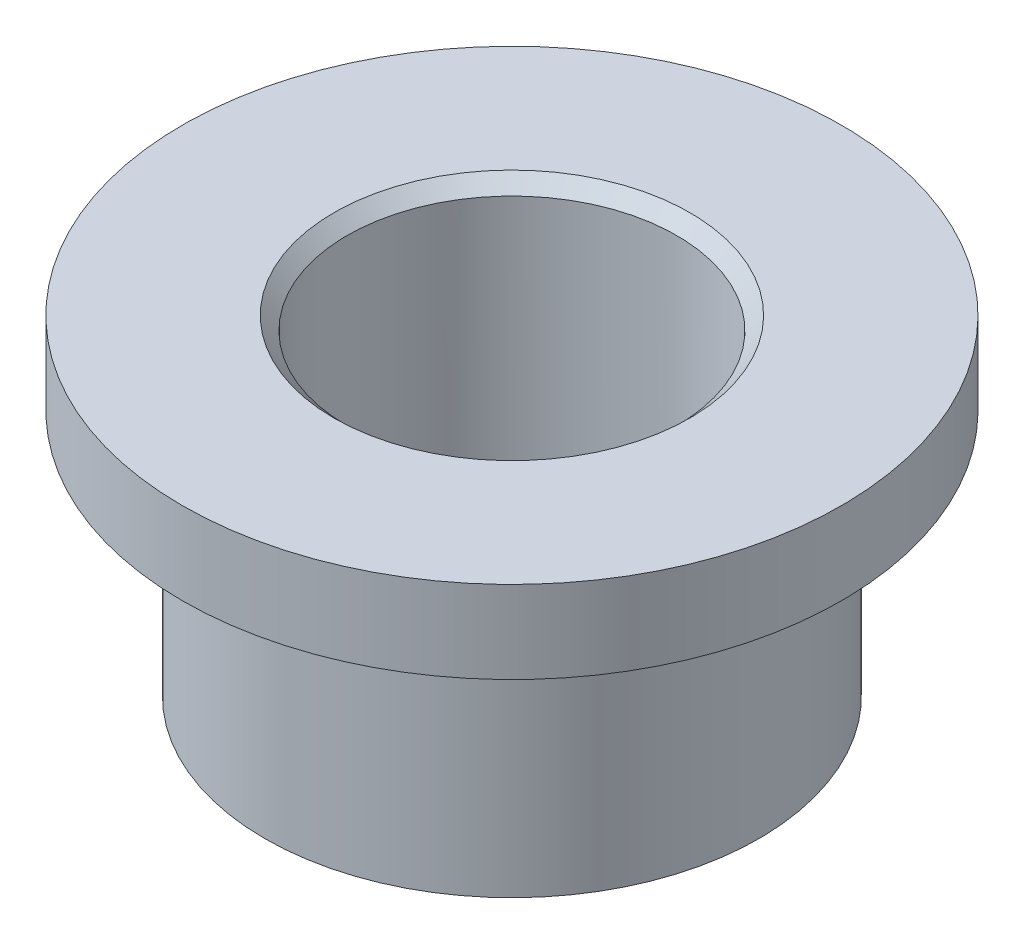
SolidWorks part; units mm, degrees
material "Tin Bearing Bronze"
ref_plane "Front Plane" through (0, 0, 0) normal (0, 0, 1) x (1, 0, 0)
ref_plane "Top Plane" through (0, 0, 0) normal (0, 1, 0) x (1, 0, 0)
ref_plane "Right Plane" through (0, 0, 0) normal (1, 0, 0) x (0, 0, -1)
sketch "Sketch1" plane through (0, 0, 0) normal (0, 0, 1) x (1, 0, 0)
  line L0 (-3.175, 3.175) -> (-6.35, 3.175)
  line L1 (-6.35, 3.175) -> (-6.35, 1.5875)
  line L2 (-6.35, 1.5875) -> (-4.7625, 1.5875)
  line L3 (-4.7625, 1.5875) -> (-4.7625, -3.175)
  line L4 (-4.7625, -3.175) -> (-3.175, -3.175)
  line L5 (-3.175, -3.175) -> (-3.175, 3.175)
  line L6 (0, 6.35) -> (0, -6.35) construction
  point P2 (-3.175, 0)
  dimension "D1" = 6.35
  dimension "D2" = 3.175
  dimension "D3" = 4.7625
  dimension "D4" = 1.5875
  dimension "D5" = 12.7
revolve "Revolve1" add sketch "Sketch1" angle 360 about L6
chamfer "Chamfer1" distance 0.254 angle 45 2 edges at (0, 3.175, 3.175) (0, -3.175, 3.175)
